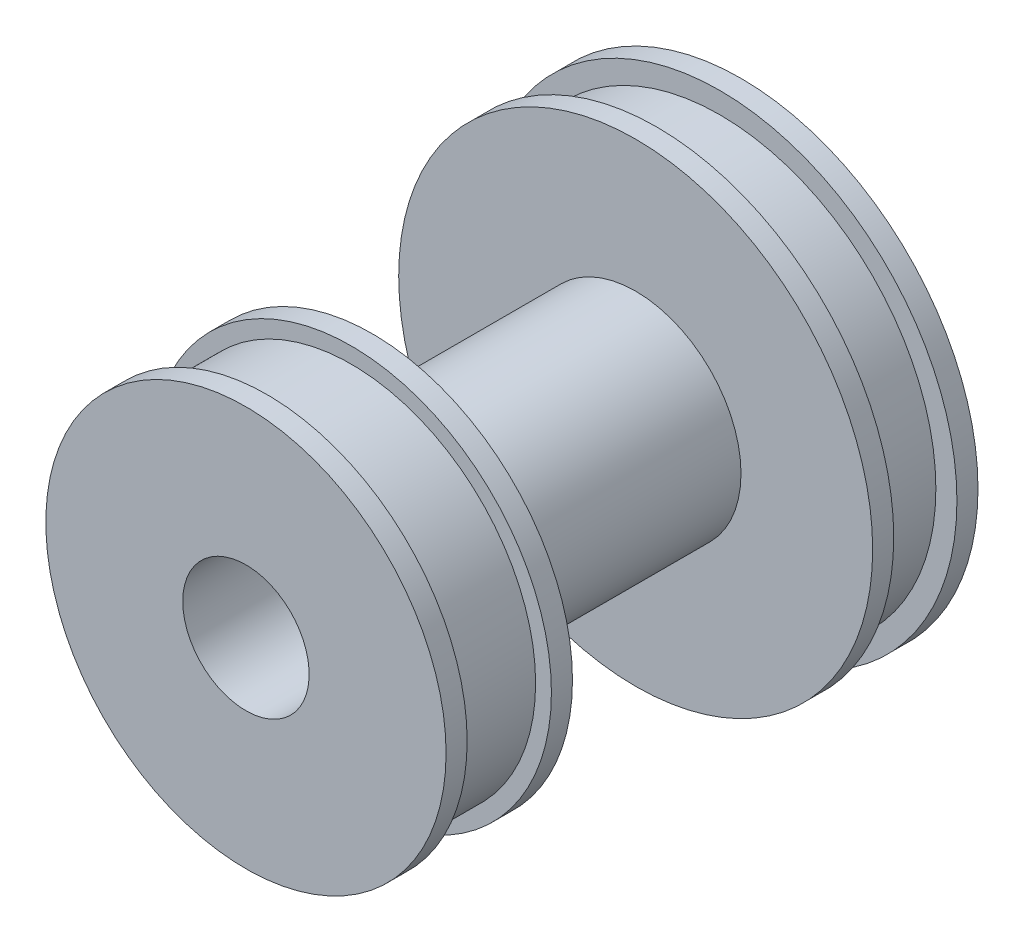
SolidWorks part; units mm, degrees
ref_plane "Vorne" through (0, 0, 0) normal (0, 0, 1) x (1, 0, 0)
ref_plane "Oben" through (0, 0, 0) normal (0, 1, 0) x (1, 0, 0)
ref_plane "Rechts" through (0, 0, 0) normal (1, 0, 0) x (0, 0, -1)
ref_plane "E_Boden" through (0, 1, 0) normal (0, 1, 0) x (1, 0, 0)
sketch "Skizze1" plane through (0, 0, 0) normal (0, 0, 1) x (1, 0, 0)
  line L0 (0, -37.3227) -> (0, 48.2798) construction
  line L1 (-67.1123, 0) -> (65.2861, 0) construction
  circle A0 centre (0, 0) radius 22.5
  dimension "D1" = 45
extrude "Seite1" add sketch "Skizze1" along normal blind 2
sketch "Skizze2" plane through (0, 0, 0) normal (0, 0, 1) x (1, 0, 0)
  circle A0 centre (0, 0) radius 20.5
  dimension "D1" = 41
extrude "Lauffläche" add sketch "Skizze2" along normal blind 8
sketch "Skizze5" plane through (0, 0, 8) normal (0, 0, 1) x (1, 0, 0)
  circle A0 centre (0, 0) radius 22.5
extrude "Seite 2" add sketch "Skizze5" along normal blind 2
sketch "Skizze7" plane through (0, 0, 0) normal (0, 0, 1) x (1, 0, 0)
  circle A0 centre (0, 0) radius 2.5
  dimension "D1" = 5
extrude "Bohrung" cut sketch "Skizze7" along normal blind 100 and the other way through all
sketch "Skizze9" plane through (0, 0, 10) normal (0, 0, 1) x (1, 0, 0)
  circle A0 centre (0, 0) radius 10
  dimension "D1" = 20
extrude "Zapfen" add sketch "Skizze9" along normal blind 25
sketch "Skizze10" plane through (0, 0, 35) normal (0, 0, 1) x (1, 0, 0)
  line L0 (0, 19) -> (0, -19) construction
  line L1 (-19, 0) -> (19, 0) construction
  circle A0 centre (0, 0) radius 19
  dimension "D1" = 38
extrude "Seitenteil3" add sketch "Skizze10" along normal blind 2
sketch "Skizze12" plane through (0, 0, 37) normal (0, 0, 1) x (1, 0, 0)
  circle A0 centre (0, 0) radius 17.5
  dimension "D1" = 35
extrude "Zahnfläche" add sketch "Skizze12" along normal blind 8
sketch "Skizze13" plane through (0, 0, 45) normal (0, 0, 1) x (1, 0, 0)
  circle A0 centre (0, 0) radius 19
  dimension "D1" = 38
extrude "Seitenteil4" add sketch "Skizze13" along normal blind 2
hole_wizard "Ø12.0 (12) Durchmesser Bohrung1" positions "Skizze15" profile "Skizze17" hole size "Ø12.0" standard "DIN" end condition through all
sketch "Skizze15" plane through (0, 0, 0) normal (0, 0, -1) x (-1, 0, 0)
  point P0 (0, 0)
sketch "Skizze17" plane through (0, 0, 0) normal (1, 0, 0) x (0, 1, 0)
  line L0 (0, 0) -> (0, 47)
  line L1 (0, 47) -> (6, 47)
  line L2 (6, 47) -> (6, 0)
  line L5 (6, 0) -> (0, 0)
  line L11 (0, -6.35) -> (0, 107.95) construction
  dimension "Bohrerdurchmesser" = 12
  dimension "Bohrungstiefe" = 47
